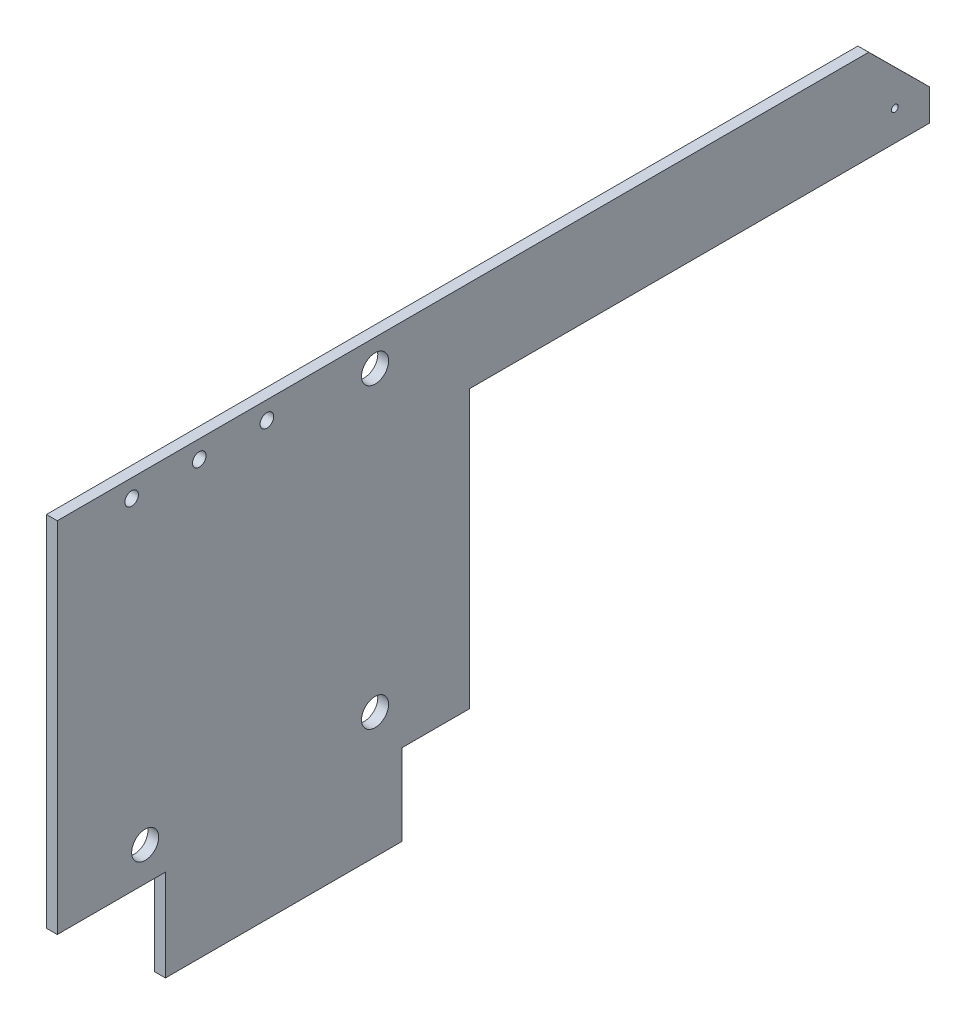
SolidWorks part; units mm, degrees
ref_plane "Front Plane" through (0, 0, 0) normal (0, 0, 1) x (1, 0, 0)
ref_plane "Top Plane" through (0, 0, 0) normal (0, 1, 0) x (1, 0, 0)
ref_plane "Right Plane" through (0, 0, 0) normal (1, 0, 0) x (0, 0, -1)
sketch "Sketch1" plane through (0, 0, 0) normal (1, 0, 0) x (0, 0, -1)
  line L0 (0, 0) -> (0, 53)
  line L1 (0, 53) -> (120, 53)
  line L2 (120, 53) -> (129, 44.0634)
  line L3 (129, 44.0634) -> (129, 39.4234)
  line L4 (129, 39.4234) -> (61, 39.4234)
  line L5 (61, 39.4234) -> (61, -1.5639)
  line L6 (61, -1.5639) -> (51, -1.5639)
  line L7 (51, -1.5639) -> (51, -13.5639)
  line L8 (51, -13.5639) -> (16, -13.5639)
  line L9 (16, -13.5639) -> (16, 0)
  line L10 (16, 0) -> (0, 0)
  line L11 (129.6211, 49.683) -> (126.503, 46.5428) construction
  line L12 (126.503, 46.5428) -> (118.343, 38.325) construction
  circle A0 centre (13, 5) radius 2
  circle A1 centre (47, 5) radius 2
  circle A2 centre (47, 49) radius 2
  circle A3 centre (11, 50.35) radius 1
  circle A4 centre (21, 50.35) radius 1
  circle A5 centre (31, 50.35) radius 1
  circle A6 centre (123.8618, 43.8829) radius 0.5
  circle A7 centre (11, 50.35) radius 0.5 construction
  circle A8 centre (21, 50.35) radius 0.5 construction
  circle A9 centre (31, 50.35) radius 0.5 construction
  circle A12 centre (47, 49) radius 2 construction
  circle A13 centre (47, 5) radius 2 construction
  circle A14 centre (13, 5) radius 2 construction
  circle A15 centre (123.8618, 43.8829) radius 0.5 construction
  point P28 (0, 0)
  point P29 (0, 0)
  point P32 (0, 0)
  point P36 (0, 0)
  point P37 (0, 0)
  point P40 (0, 0)
  point P43 (0, 0)
  dimension "D1" = 2
  dimension "D2" = 120
  dimension "D3" = 16
  dimension "D4" = 10
  dimension "D5" = 35
  dimension "D6" = 68
  dimension "D7" = 53
  dimension "D8" = 13.5639
  dimension "D9" = 40.9874
  dimension "D10" = 12
extrude "Boss-Extrude1" add sketch "Sketch1" along normal blind 1.6
